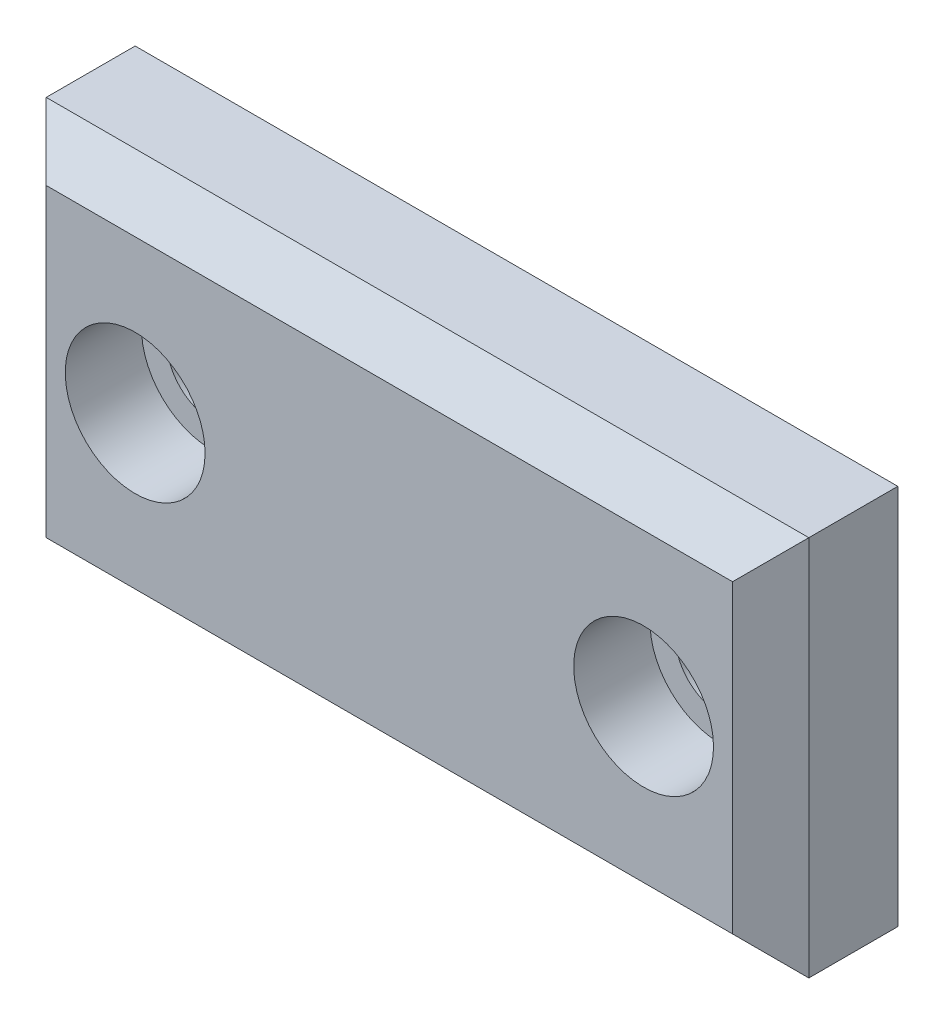
SolidWorks part; units mm, degrees
other "细节项目8"
ref_plane "前视基准面" through (0, 0, 0) normal (0, 0, 1) x (1, 0, 0)
ref_plane "上视基准面" through (0, 0, 0) normal (0, 1, 0) x (1, 0, 0)
ref_plane "右视基准面" through (0, 0, 0) normal (1, 0, 0) x (0, 0, -1)
sketch "草图1" plane through (0, 0, 0) normal (0, 0, 1) x (1, 0, 0)
  line L1 (-30, -15) -> (30, -15)
  line L2 (-30, -15) -> (-30, 15)
  line L3 (-30, 15) -> (30, 15)
  line L4 (30, -15) -> (30, 15)
  line L5 (-30, -15) -> (30, 15) construction
  line L6 (-30, 15) -> (30, -15) construction
  point P0 (0, 0)
  dimension "D1" = 60
  dimension "D2" = 30
extrude "凸台-拉伸1" add sketch "草图1" along normal blind 10
chamfer "倒角1" distance 3 angle 45 4 edges at (0, -15, 10) (-30, 0, 10) (0, 15, 10) (30, 0, 10)
sketch "草图2" plane through (0, 0, 10) normal (0, 0, 1) x (1, 0, 0)
  line L0 (-30, -15) -> (-30, 15) construction
  line L1 (30, 15) -> (30, -15) construction
  line L2 (30, -15) -> (-30, -15) construction
  circle A0 centre (-20, 0) radius 3.5
  circle A1 centre (20, 0) radius 3.5
  dimension "D1" = 7
  dimension "D2" = 7
  dimension "D3" = 10
  dimension "D4" = 10
  dimension "D5" = 15
  dimension "D6" = 15
extrude "切除-拉伸1" cut sketch "草图2" against normal through all
sketch "草图3" plane through (0, 0, 10) normal (0, 0, 1) x (1, 0, 0)
  circle A0 centre (-20, 0) radius 5.5
  circle A1 centre (20, 0) radius 5.5
  dimension "D1" = 11
  dimension "D2" = 11
extrude "切除-拉伸2" cut sketch "草图3" against normal blind 6
